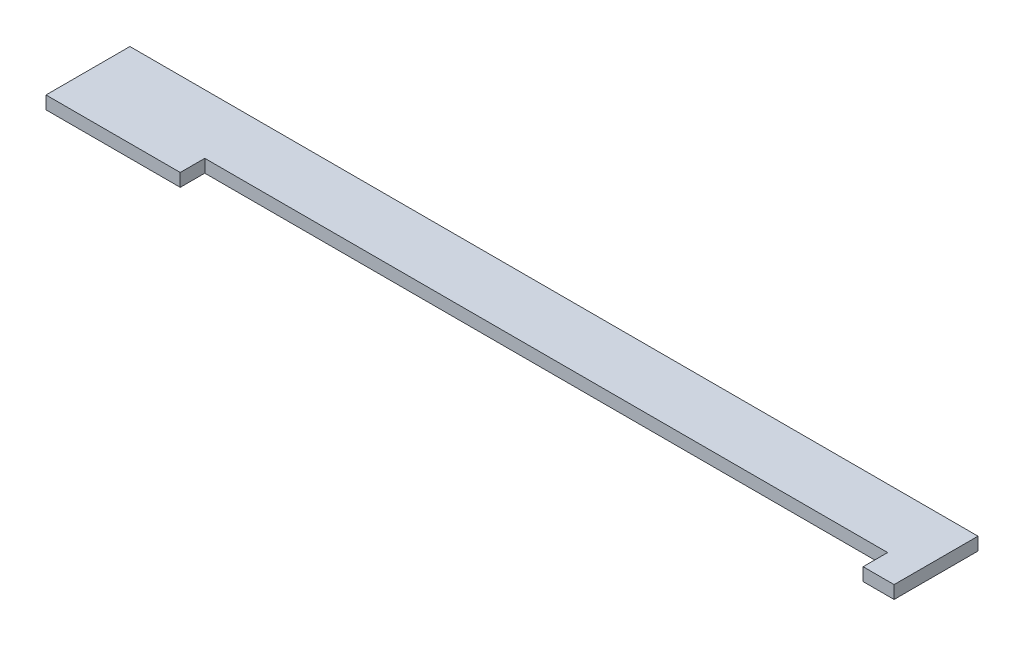
SolidWorks part; units mm, degrees
material "Mahogany"
ref_plane "Front Plane" through (0, 0, 0) normal (0, 0, 1) x (1, 0, 0)
ref_plane "Top Plane" through (0, 0, 0) normal (0, 1, 0) x (1, 0, 0)
ref_plane "Right Plane" through (0, 0, 0) normal (1, 0, 0) x (0, 0, -1)
sketch "Sketch1" plane through (0, 0, 0) normal (0, 1, 0) x (1, 0, 0)
  line L0 (-62.1965, 37.3691) -> (-62.1965, -27.6309)
  line L1 (-62.1965, -27.6309) -> (41.8035, -27.6309)
  line L2 (41.8035, -27.6309) -> (41.8035, -8.6309)
  line L3 (41.8035, -8.6309) -> (570.8035, -8.6309)
  line L4 (570.8035, -8.6309) -> (570.8035, -27.6309)
  line L5 (570.8035, -27.6309) -> (594.8035, -27.6309)
  line L6 (594.8035, -27.6309) -> (594.8035, 37.3691)
  line L7 (594.8035, 37.3691) -> (-62.1965, 37.3691)
  dimension "D1" = 65
  dimension "D2" = 46
  dimension "D3" = 24
  dimension "D4" = 529
  dimension "D5" = 104
extrude "Boss-Extrude1" add sketch "Sketch1" along normal blind 10
